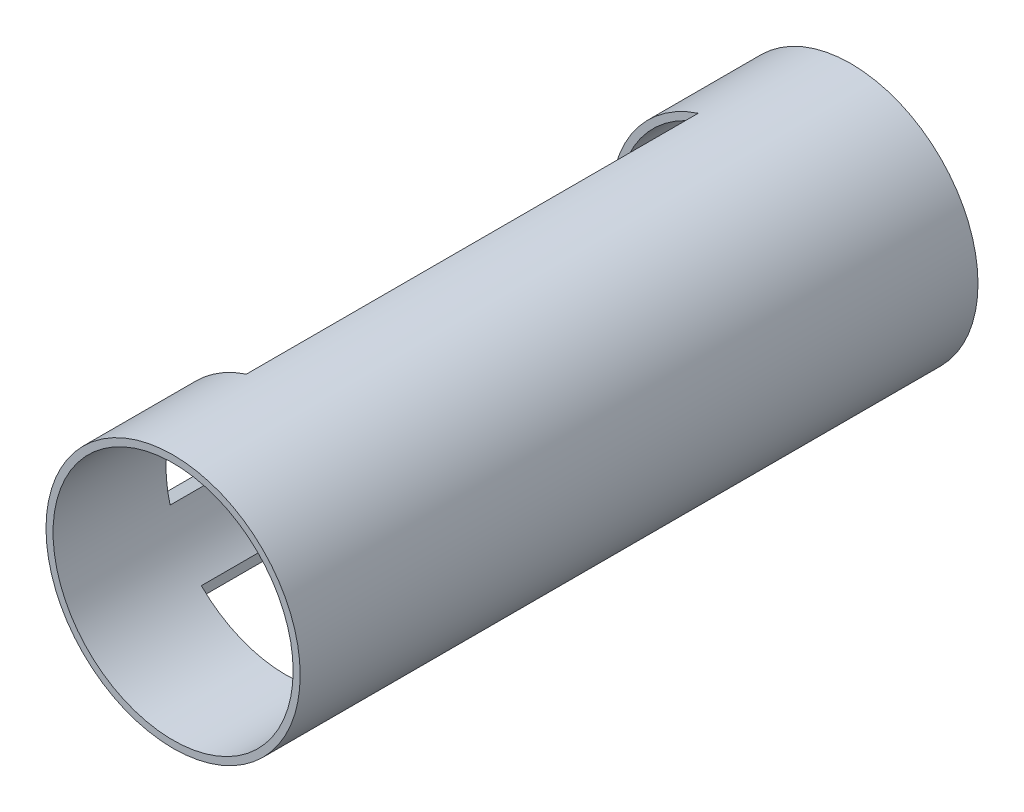
SolidWorks part; units mm, degrees
ref_plane "Front Plane" through (0, 0, 0) normal (0, 0, 1) x (1, 0, 0)
ref_plane "Top Plane" through (0, 0, 0) normal (0, 1, 0) x (1, 0, 0)
ref_plane "Right Plane" through (0, 0, 0) normal (1, 0, 0) x (0, 0, -1)
sketch "Sketch1" plane through (0, 0, 0) normal (0, 0, 1) x (1, 0, 0)
  circle A0 centre (0, 0) radius 53.975
  circle A1 centre (0, 0) radius 57.15
  dimension "D1" = 107.95
  dimension "D2" = 3.175
extrude "Extrude1" add sketch "Sketch1" along normal blind 304.8
sketch "Sketch2" plane through (0, 0, 0) normal (0, 1, 0) x (1, 0, 0)
  line L0 (0, 0) -> (0, -304.8) construction
  line L1 (-38.1, -50.8) -> (38.1, -50.8)
  line L2 (-38.1, -50.8) -> (-38.1, -254)
  line L3 (-38.1, -254) -> (38.1, -254)
  line L4 (38.1, -50.8) -> (38.1, -254)
  line L5 (-57.15, -304.8) -> (57.15, -304.8) construction
  point P4 (0, -50.8)
  point P10 (0, -152.4)
  point P11 (-38.1, -152.4)
  dimension "D1" = 76.2
  dimension "D2" = 203.2
extrude "Extrude2" cut sketch "Sketch2" against normal through all
ref_plane "Plane1" through (0, 0, 0) normal (0.866, -0.5, 0) x (0, 0, -1)
sketch "Sketch3" plane through (0, 0, 0) normal (0.866, -0.5, 0) x (0, 0, -1)
  line L0 (0, 0) -> (-304.8, 0) construction
  line L1 (-50.8, 38.1) -> (-254, 38.1)
  line L2 (-50.8, 38.1) -> (-50.8, -38.1)
  line L3 (-50.8, -38.1) -> (-254, -38.1)
  line L4 (-254, 38.1) -> (-254, -38.1)
  line L5 (-304.8, 57.15) -> (-304.8, -57.15) construction
  point P9 (-152.4, 0)
  point P10 (-152.4, 38.1)
  point P11 (-50.8, 0)
  dimension "D1" = 76.2
  dimension "D2" = 203.2
extrude "Extrude3" cut sketch "Sketch3" against normal through all
